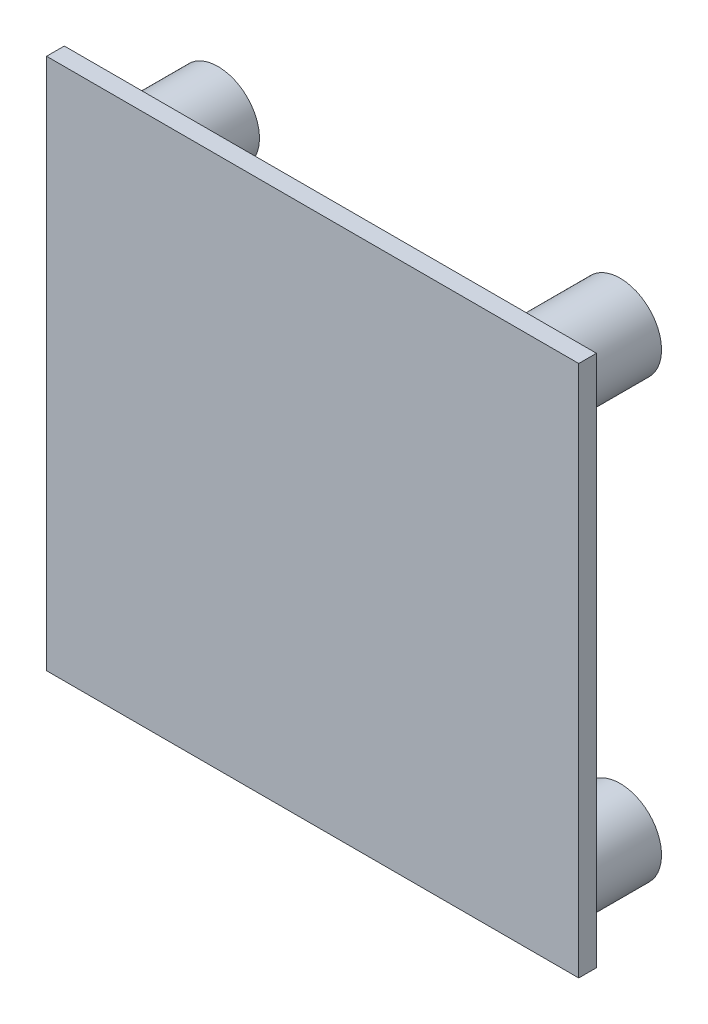
SolidWorks part; units mm, degrees
ref_plane "Спереди" through (0, 0, 0) normal (0, 0, 1) x (1, 0, 0)
ref_plane "Сверху" through (0, 0, 0) normal (0, 1, 0) x (1, 0, 0)
ref_plane "Справа" through (0, 0, 0) normal (1, 0, 0) x (0, 0, -1)
sketch "Эскиз1" plane through (0, 0, 0) normal (0, 0, 1) x (1, 0, 0)
  line L1 (0, 0) -> (45, 0)
  line L2 (0, 0) -> (0, 45)
  line L3 (0, 45) -> (45, 45)
  line L4 (45, 0) -> (45, 45)
  dimension "D1" = 45
  dimension "D2" = 45
extrude "Бобышка-Вытянуть1" add sketch "Эскиз1" along normal blind 1.5
sketch "Эскиз2" plane through (0, 0, 0) normal (0, 0, -1) x (-1, 0, 0)
  line L0 (-40, 41) -> (-40, 4) construction
  line L1 (-6, 39.5) -> (-6, 6.5) construction
  line L2 (-45, 0) -> (-45, 45) construction
  line L3 (-6, 39.5) -> (-45, 39.5) construction
  line L4 (-6, 39.5) -> (-6, 45) construction
  line L5 (-45, 45) -> (0, 45) construction
  line L6 (-6, 45) -> (-6, 39.5) construction
  line L7 (-6, 39.5) -> (0, 39.5) construction
  line L8 (0, 45) -> (0, 0) construction
  circle A0 centre (-40, 4) radius 1.5
  circle A1 centre (-6, 6.5) radius 1.5
  circle A2 centre (-6, 39.5) radius 1.5
  circle A3 centre (-40, 41) radius 1.5
  circle A4 centre (-40, 41) radius 3.5
  circle A5 centre (-6, 39.5) radius 3.5
  circle A6 centre (-40, 4) radius 3.5
  circle A7 centre (-6, 6.5) radius 3.5
  point P15 (0, 0)
  point P17 (-38, 11.9058)
  dimension "D1" = 3
  dimension "D6" = 7
  dimension "D2" = 37
  dimension "D3" = 1.5
  dimension "D4" = 5.5
  dimension "D5" = 6
  dimension "D7" = 33
  dimension "D8" = 5
extrude "Бобышка-Вытянуть2" add sketch "Эскиз2" along normal blind 7
